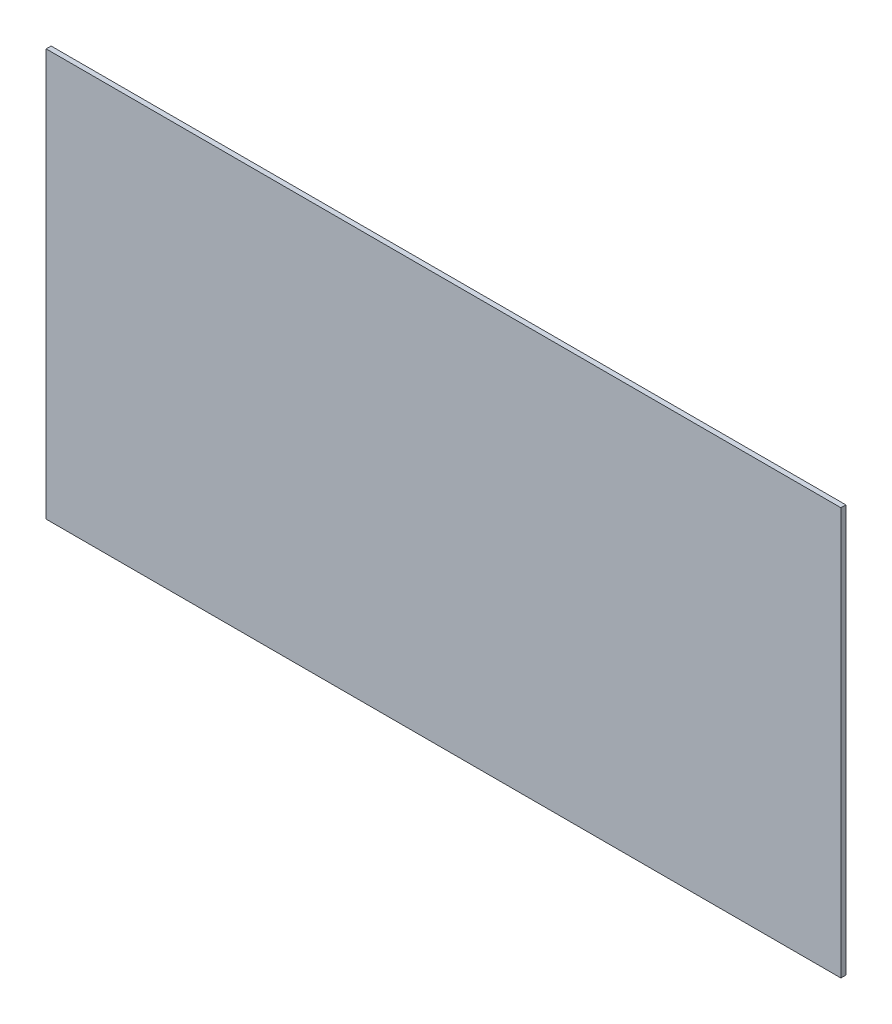
SolidWorks part; units mm, degrees
ref_plane "Front Plane" through (0, 0, 0) normal (0, 0, 1) x (1, 0, 0)
ref_plane "Top Plane" through (0, 0, 0) normal (0, 1, 0) x (1, 0, 0)
ref_plane "Right Plane" through (0, 0, 0) normal (1, 0, 0) x (0, 0, -1)
sketch "Sketch1" plane through (0, 0, 0) normal (0, 0, 1) x (1, 0, 0)
  line L1 (-254, -130.175) -> (254, -130.175)
  line L2 (-254, -130.175) -> (-254, 130.175)
  line L3 (-254, 130.175) -> (254, 130.175)
  line L4 (254, -130.175) -> (254, 130.175)
  line L5 (-254, -130.175) -> (254, 130.175) construction
  line L6 (-254, 130.175) -> (254, -130.175) construction
  point P0 (0, 0)
  dimension "D1" = 508
  dimension "D2" = 260.35
extrude "Boss-Extrude1" add sketch "Sketch1" along normal blind 3.175
